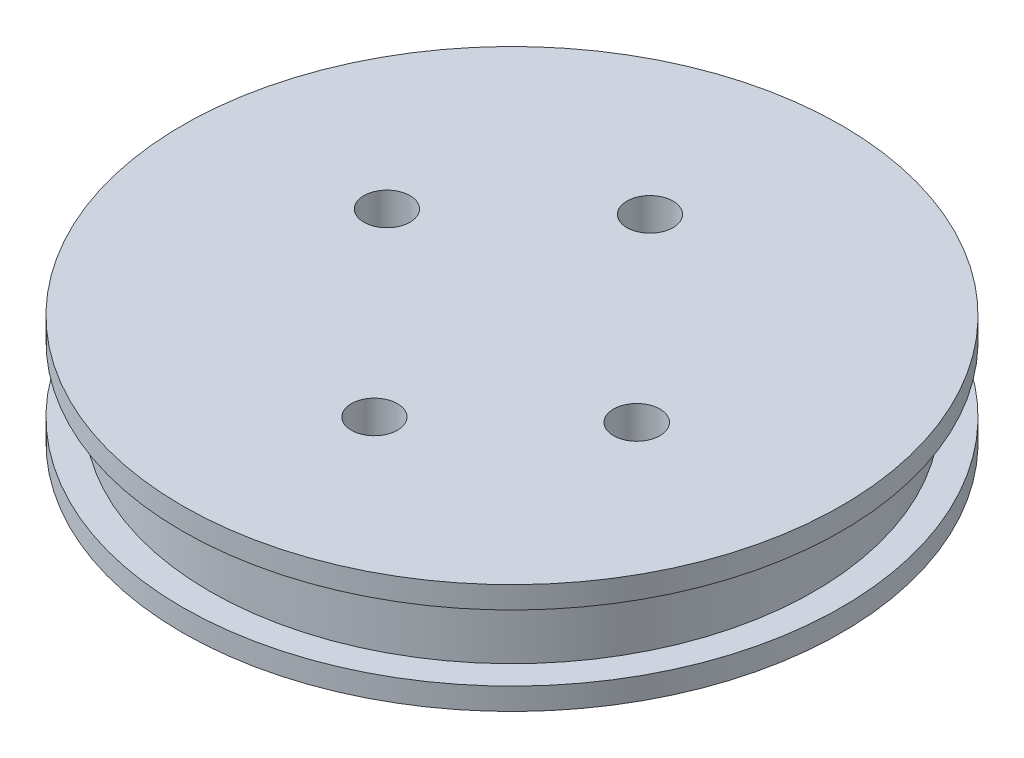
SolidWorks part; units mm, degrees
ref_plane "Спереди" through (0, 0, 0) normal (0, 0, 1) x (1, 0, 0)
ref_plane "Сверху" through (0, 0, 0) normal (0, 1, 0) x (1, 0, 0)
ref_plane "Справа" through (0, 0, 0) normal (1, 0, 0) x (0, 0, -1)
other "Configuration Table"
sketch "Эскиз1" plane through (0, 0, 0) normal (0, 1, 0) x (1, 0, 0)
  circle A2 centre (0, 0) radius 27.5
extrude "Бобышка-Вытянуть5" add sketch "Эскиз1" along normal blind 6
sketch "Эскиз8" plane through (0, 6, 0) normal (0, 1, 0) x (1, 0, 0)
  circle A0 centre (0, 0) radius 30
extrude "Бобышка-Вытянуть6" add sketch "Эскиз8" along normal blind 2
sketch "Эскиз9" plane through (0, 0, 0) normal (0, -1, 0) x (1, 0, 0)
  circle A0 centre (0, 0) radius 30
extrude "Бобышка-Вытянуть7" add sketch "Эскиз9" along normal blind 2
sketch "Эскиз10" plane through (0, 8, 0) normal (0, 1, 0) x (1, 0, 0)
  circle A0 centre (0, 0) radius 10.2705
sketch "Эскиз11" plane through (0, 8, 0) normal (0, 1, 0) x (1, 0, 0)
  circle A0 centre (0, 0) radius 12.3821 construction
sketch "Эскиз12" plane through (0, 8, 0) normal (0, 1, 0) x (1, 0, 0)
  line L2 (0, 0) -> (-3.8027, -14.5247) construction
  line L3 (-18.3136, -10.7256) -> (10.7082, -18.3238) construction
  circle A2 centre (14.0955, -2.7425) radius 2.11
  circle A6 centre (1.7268, -14.2556) radius 2.1
  circle A7 centre (-14.1007, 2.7157) radius 2.1
  circle A8 centre (-1.6998, 14.2589) radius 2.1
extrude "Вырез-Вытянуть1" cut sketch "Эскиз12" against normal through all both and the other way through all
